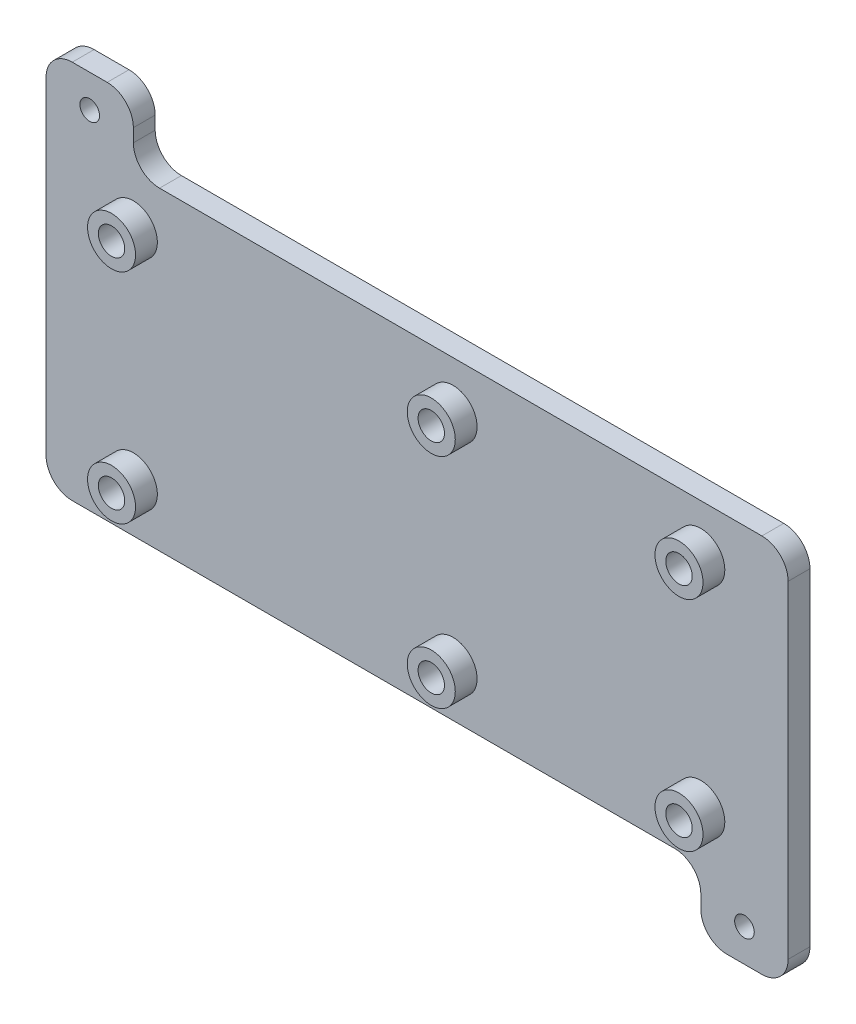
SolidWorks part; units mm, degrees
material "Custom Plastic"
ref_plane "X-Y Datum" through (0, 0, 0) normal (0, 0, 1) x (1, 0, 0)
ref_plane "X-Z Datum" through (0, 0, 0) normal (0, 1, 0) x (1, 0, 0)
ref_plane "Y-Z Datum" through (0, 0, 0) normal (1, 0, 0) x (0, 0, -1)
sketch "Sketch1" plane through (0, 0, 0) normal (0, 0, 1) x (1, 0, 0)
  line L1 (-70.0024, 29.9974) -> (70.0024, 29.9974) construction
  line L2 (-70.0024, 29.9974) -> (-70.0024, -29.9974) construction
  line L3 (-70.0024, -29.9974) -> (70.0024, -29.9974) construction
  line L4 (70.0024, 29.9974) -> (70.0024, -29.9974) construction
  line L5 (-70.0024, 29.9974) -> (70.0024, -29.9974) construction
  line L6 (-70.0024, -29.9974) -> (70.0024, 29.9974) construction
  line L7 (-85, 36) -> (85, 36)
  line L8 (-85, 36) -> (-85, -36)
  line L9 (-85, -36) -> (85, -36)
  line L10 (85, 36) -> (85, -36)
  line L11 (-85, 36) -> (85, -36) construction
  line L12 (-85, -36) -> (85, 36) construction
  point P0 (0, 0)
  point P6 (0, 0)
  dimension "D1" = 140.0048
  dimension "D2" = 59.9948
  dimension "D3" = 170
  dimension "D4" = 72
extrude "Boss-Extrude1" add sketch "Sketch1" along normal blind 5
sketch "Sketch2" plane through (0, 0, 5) normal (0, 0, 1) x (1, 0, 0)
  circle A0 centre (65, 25) radius 3.025
  circle A1 centre (65, -25) radius 3.025
  circle A2 centre (8.25, 25) radius 3.025
  circle A3 centre (8.25, -25) radius 3.025
  circle A4 centre (-65, 25) radius 3.025
  circle A5 centre (-65, -25) radius 3.025
  circle A6 centre (65, 25) radius 5.5
  circle A7 centre (8.25, 25) radius 5.5
  circle A8 centre (-65, 25) radius 5.5
  circle A9 centre (-65, -25) radius 5.5
  circle A10 centre (8.25, -25) radius 5.5
  circle A11 centre (65, -25) radius 5.5
  point P0 (65, -25)
  point P1 (65, 25)
  point P3 (8.25, 25)
  point P5 (8.25, -25)
  point P7 (-65, 25)
  point P9 (-65, -25)
  dimension "D1" = 6.05
  dimension "D2" = 11
extrude "Boss-Extrude2" add sketch "Sketch2" along normal blind 5
sketch "Sketch3" plane through (0, 0, 5) normal (0, 0, 1) x (1, 0, 0)
  line L0 (85, -36) -> (65, -51) construction
  line L1 (-85, 36) -> (-65, 36)
  line L2 (-85, 36) -> (-85, 51)
  line L3 (-85, 51) -> (-65, 51)
  line L4 (-65, 36) -> (-65, 51)
  line L5 (85, -36) -> (65, -36)
  line L6 (85, -36) -> (85, -51)
  line L7 (85, -51) -> (65, -51)
  line L8 (65, -36) -> (65, -51)
  line L9 (-65, 51) -> (-85, 36)
  point P10 (75, -43.5)
  point P11 (-75, 43.5)
  line M17 (85, 36) -> (-85, 36)
  line M19 (-85, -36) -> (85, -36)
  dimension "D1" = 15
  dimension "D2" = 20
  dimension "D3" = 15
  dimension "D4" = 20
extrude "Boss-Extrude3" add sketch "Sketch3" against normal blind 5 contours L9 L3 L2 | L4 L9 M17 | L0 L8 M19 | L6 L0 L7
fillet "Fillet1" radius 6 8 edges at (65, -36, 2.5) (65, -51, 2.5) (85, -51, 2.5) (85, 36, 2.5) (-65, 36, 2.5) (-65, 51, 2.5) (-85, 51, 2.5) (-85, -36, 2.5)
hole_wizard "M4 Clearance Hole1" positions "Sketch4" profile "Sketch5" hole size "M4" standard "ANSI Metric" end condition through all
sketch "Sketch4" plane through (0, 0, 5) normal (0, 0, 1) x (1, 0, 0)
  point P0 (-75, 43.5)
  point P3 (75, -43.5)
sketch "Sketch5" plane through (-75, 43.5, 5) normal (1, 0, 0) x (0, -1, 0)
  line L0 (0, 0) -> (0, 5)
  line L1 (0, 5) -> (2.25, 5)
  line L2 (2.25, 5) -> (2.25, 0)
  line L5 (2.25, 0) -> (0, 0)
  line L11 (0, -6.35) -> (0, 107.95) construction
  dimension "Thru Hole Dia." = 4.5
  dimension "Thru Hole Depth" = 5
